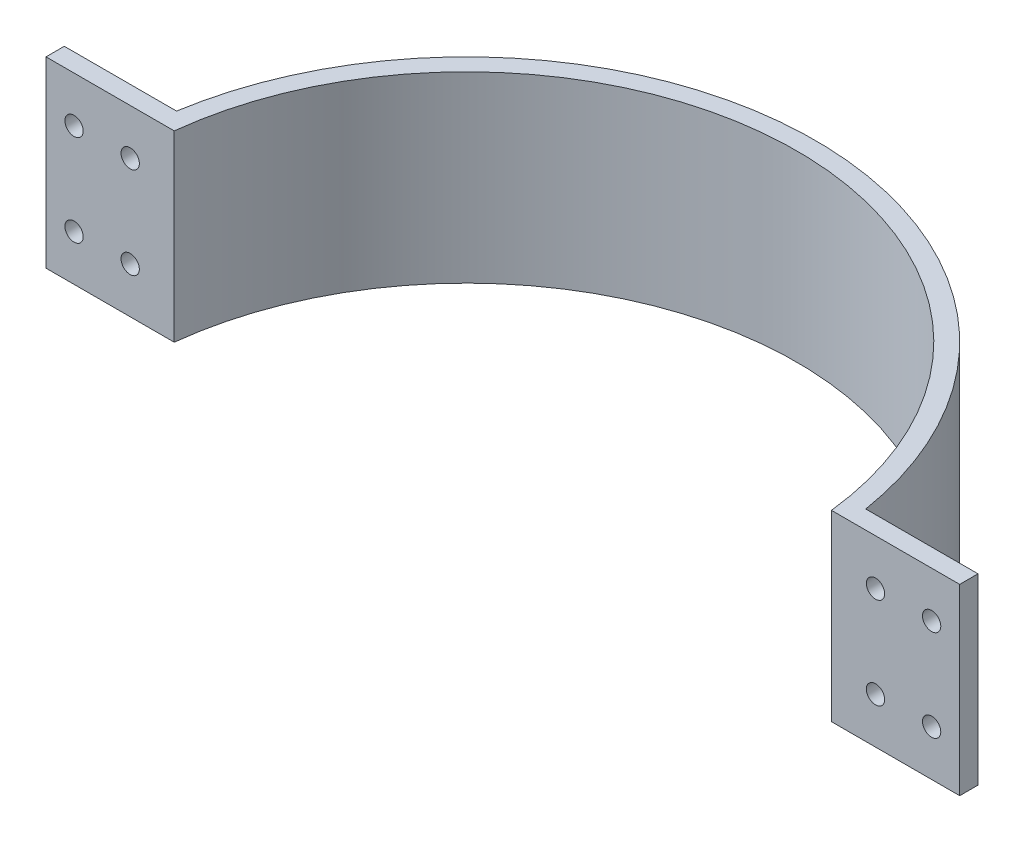
SolidWorks part; units mm, degrees
ref_plane "Front Plane" through (0, 0, 0) normal (0, 0, 1) x (1, 0, 0)
ref_plane "Top Plane" through (0, 0, 0) normal (0, 1, 0) x (1, 0, 0)
ref_plane "Right Plane" through (0, 0, 0) normal (1, 0, 0) x (0, 0, -1)
sketch "Sketch1" plane through (0, 0, 0) normal (0, 1, 0) x (1, 0, 0)
  line L0 (0, 0) -> (-102, 0)
  line L3 (-119.5416, 19.05) -> (-158.4819, 19.05)
  line L5 (-158.4819, 19.05) -> (-158.4819, 12.7)
  line L7 (-113.9947, 12.7) -> (-158.4819, 12.7)
  line L8 (-114.7, 0) -> (-121.05, 0)
  line L10 (-113.9947, -12.7) -> (-158.4819, -12.7)
  line L11 (-158.4819, -19.05) -> (-158.4819, -12.7)
  line L12 (-119.5416, -19.05) -> (-158.4819, -19.05)
  line L13 (0, -19.05) -> (0, 19.05)
  line L14 (119.5416, -19.05) -> (158.4819, -19.05)
  line L15 (158.4819, -19.05) -> (158.4819, -12.7)
  line L16 (113.9947, -12.7) -> (158.4819, -12.7)
  line L17 (113.9947, 12.7) -> (158.4819, 12.7)
  line L18 (158.4819, 19.05) -> (158.4819, 12.7)
  line L19 (119.5416, 19.05) -> (158.4819, 19.05)
  circle A0 centre (0, 0) radius 102
  circle A1 centre (0, 0) radius 114.7
  arc A2 (-120.3819, 12.7) -> (-120.3819, -12.7) centre (0, 0) ccw
  circle A3 centre (0, 0) radius 121.05 construction
  arc A4 (-119.5416, -19.05) -> (119.5416, -19.05) centre (0, 0) ccw
  arc A5 (120.3819, -12.7) -> (120.3819, 12.7) centre (0, 0) ccw
  arc A6 (119.5416, 19.05) -> (-119.5416, 19.05) centre (0, 0) ccw
  point P29 (0, 0)
  dimension "D1" = 204
  dimension "D2" = 12.7
  dimension "D6" = 38.1
  dimension "D3" = 6.35
extrude "Boss-Extrude1" add sketch "Sketch1" along normal mid plane 63.5 contours L19 A6 L3 L5 L7 A1 L17 L18
sketch "Sketch2" plane through (0, 0, -12.7) normal (0, 0, 1) x (1, 0, 0)
  line L0 (-119.5416, 0) -> (-158.4819, 0) construction
  line L1 (-113.9947, 31.75) -> (-113.9947, -31.75) construction
  line L3 (-139.0118, 0) -> (-139.0118, 31.75) construction
  line L5 (-113.9947, 31.75) -> (-158.4819, 31.75) construction
  line L6 (-113.9947, 0) -> (113.9947, 0) construction
  line L7 (113.9947, 31.75) -> (113.9947, -31.75) construction
  line L8 (0, 0) -> (0, 31.75) construction
  line L9 (113.9947, 31.75) -> (-113.9947, 31.75) construction
  line L10 (-119.5416, 31.75) -> (-119.5416, -31.75) construction
  line L11 (-113.9947, -31.75) -> (-158.4819, -31.75) construction
  line L12 (-158.4819, 31.75) -> (-158.4819, -31.75) construction
  line L13 (-139.0118, 15.875) -> (-119.5416, 15.875) construction
  circle A8 centre (-129.2767, 15.875) radius 3.175
  circle A9 centre (-148.7469, 15.875) radius 3.175
  circle A10 centre (-148.7469, -15.875) radius 3.175
  circle A11 centre (-129.2767, -15.875) radius 3.175
  circle A12 centre (129.2767, 15.875) radius 3.175
  circle A13 centre (148.7469, 15.875) radius 3.175
  circle A14 centre (129.2767, -15.875) radius 3.175
  circle A15 centre (148.7469, -15.875) radius 3.175
extrude "Cut-Extrude1" cut sketch "Sketch2" against normal through all
